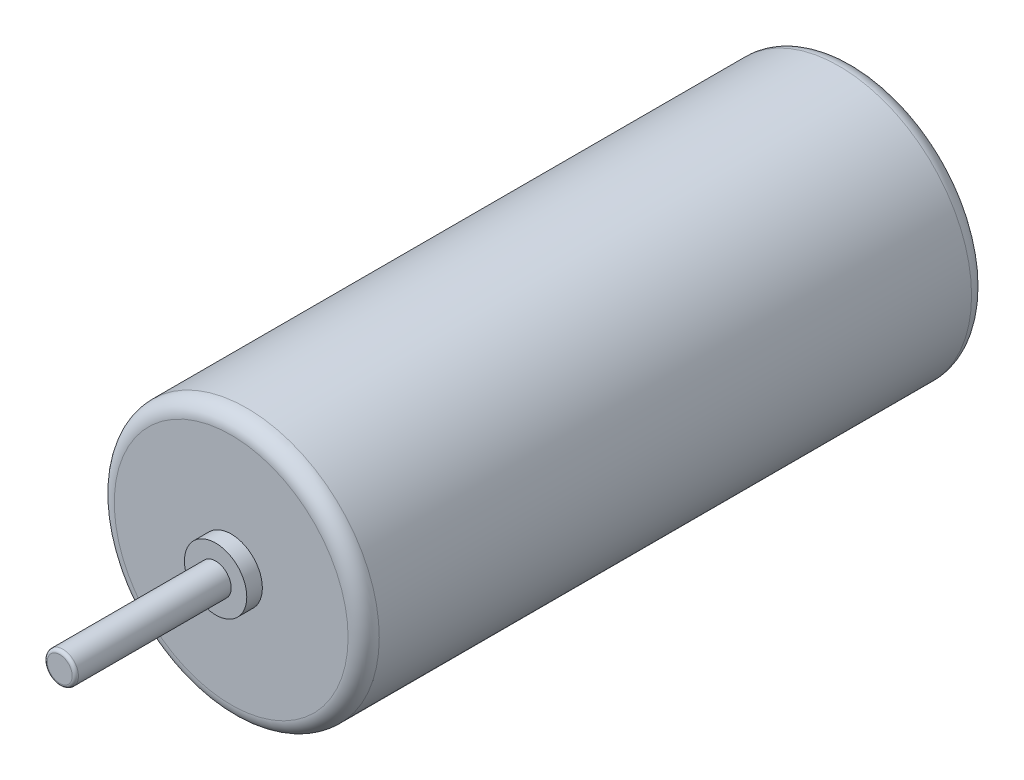
SolidWorks part; units mm, degrees
ref_plane "Front Plane" through (0, 0, 0) normal (0, 0, 1) x (1, 0, 0)
ref_plane "Top Plane" through (0, 0, 0) normal (0, 1, 0) x (1, 0, 0)
ref_plane "Right Plane" through (0, 0, 0) normal (1, 0, 0) x (0, 0, -1)
sketch "Sketch1" plane through (0, 0, 0) normal (0, 0, 1) x (1, 0, 0)
  circle A0 centre (0, 0) radius 4.25
  dimension "D1" = 8.5
extrude "Boss-Extrude1" add sketch "Sketch1" along normal blind 20
sketch "Sketch2" plane through (0, 0, 20) normal (0, 0, 1) x (1, 0, 0)
  circle A0 centre (0, 0) radius 1
  dimension "D1" = 2
extrude "Boss-Extrude2" add sketch "Sketch2" along normal blind 0.5
sketch "Sketch3" plane through (0, 0, 20.5) normal (0, 0, 1) x (1, 0, 0)
  circle A0 centre (0, 0) radius 0.5
  dimension "D1" = 1
extrude "Boss-Extrude3" add sketch "Sketch3" along normal blind 5
fillet "Fillet2" radius 0.5 1 edges at (4.25, 0, 20)
fillet "Fillet3" radius 0.1 1 edges at (0.5, 0, 25.5)
fillet "Fillet4" radius 0.5 1 edges at (4.25, 0, 0)
